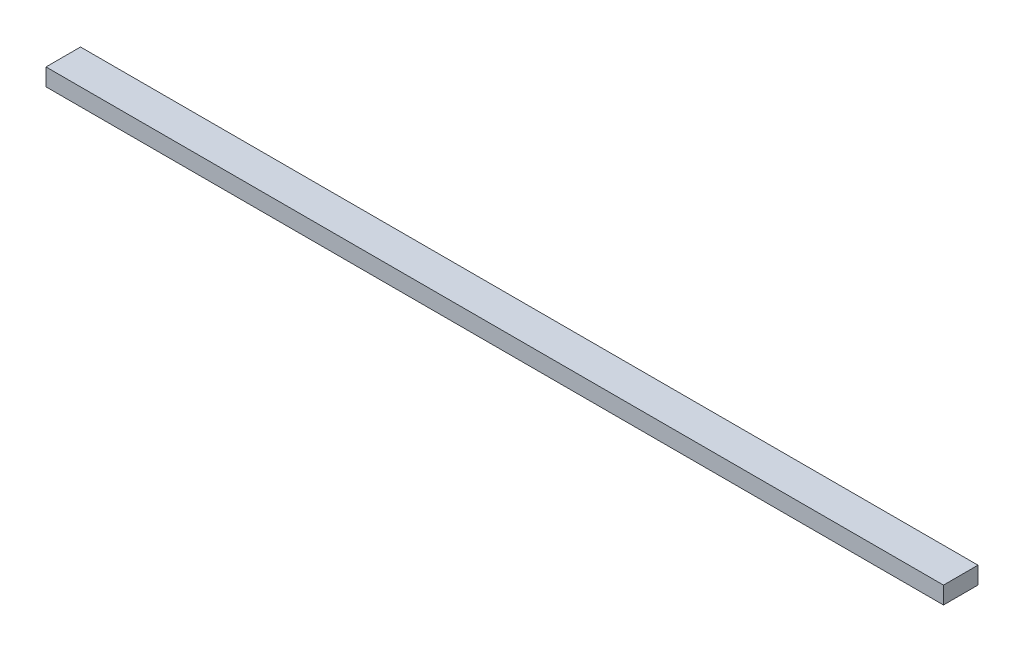
SolidWorks part; units mm, degrees
ref_plane "Alzado" through (0, 0, 0) normal (0, 0, 1) x (1, 0, 0)
ref_plane "Planta" through (0, 0, 0) normal (0, 1, 0) x (1, 0, 0)
ref_plane "Vista lateral" through (0, 0, 0) normal (1, 0, 0) x (0, 0, -1)
sketch "Croquis1" plane through (0, 0, 0) normal (0, 1, 0) x (1, 0, 0)
  line L0 (-1130.9041, -50) -> (-1130.9041, -100)
  line L1 (-1130.9041, -100) -> (169.0959, -100)
  line L2 (169.0959, -100) -> (169.0959, -50)
  line L3 (169.0959, -50) -> (-1130.9041, -50)
  dimension "D1" = 50
  dimension "D2" = 1300
extrude "Saliente-Extruir1" add sketch "Croquis1" along normal blind 25
